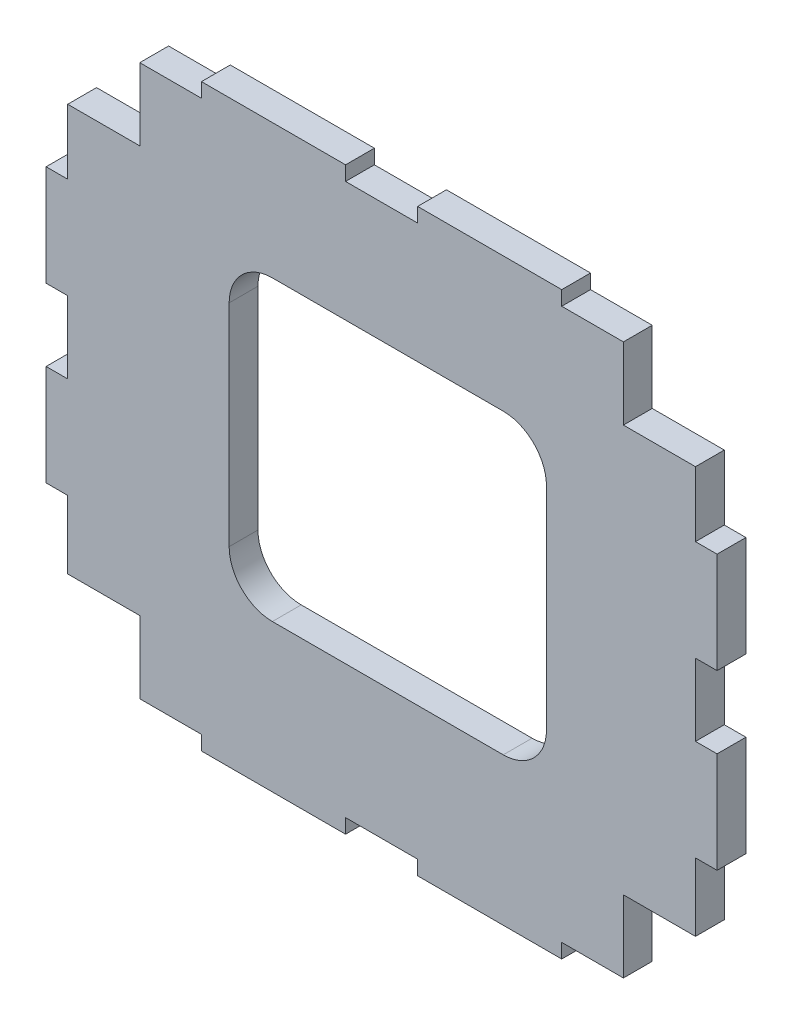
SolidWorks part; units mm, degrees
ref_plane "前视基准面" through (0, 0, 0) normal (0, 0, 1) x (1, 0, 0)
ref_plane "上视基准面" through (0, 0, 0) normal (0, 1, 0) x (1, 0, 0)
ref_plane "右视基准面" through (0, 0, 0) normal (1, 0, 0) x (0, 0, -1)
sketch "Model" plane through (0, 0, 0) normal (0, 0, 1) x (1, 0, 0)
  line L0 (45.0198, 33.9458) -> (28.9998, 33.9458)
  line L1 (28.9998, 13.2958) -> (45.0198, 13.2958)
  line L2 (48.0198, 30.9458) -> (48.0198, 16.2958)
  line L3 (25.9998, 30.9458) -> (25.9998, 16.2958)
  line L4 (19.7974, 42.2796) -> (24.0774, 42.2796)
  line L5 (24.0774, 42.2796) -> (24.0774, 43.28)
  line L6 (24.0774, 43.28) -> (34.0774, 43.28)
  line L7 (34.0774, 43.28) -> (34.0774, 42.2796)
  line L8 (34.0774, 42.2796) -> (39.0774, 42.2796)
  line L9 (39.0774, 42.2796) -> (39.0774, 43.28)
  line L10 (39.0774, 43.28) -> (49.0774, 43.28)
  line L11 (49.0774, 43.28) -> (49.0774, 42.2796)
  line L12 (49.0774, 42.2796) -> (53.3574, 42.2796)
  line L13 (19.7974, 4.0528) -> (24.0774, 4.0528)
  line L14 (24.0774, 4.0528) -> (24.0774, 3.0524)
  line L15 (24.0774, 3.0524) -> (34.0774, 3.0524)
  line L16 (34.0774, 3.0524) -> (34.0774, 4.0528)
  line L17 (34.0774, 4.0528) -> (39.0774, 4.0528)
  line L18 (39.0774, 4.0528) -> (39.0774, 3.0524)
  line L19 (39.0774, 3.0524) -> (49.0774, 3.0524)
  line L20 (49.0774, 3.0524) -> (49.0774, 4.0528)
  line L21 (49.0774, 4.0528) -> (53.3574, 4.0528)
  line L22 (13.2974, 13.7734) -> (13.2974, 20.7734)
  line L23 (13.2974, 25.7734) -> (13.2974, 32.7734)
  line L24 (14.7974, 37.2796) -> (19.7974, 37.2796)
  line L25 (19.7974, 37.2796) -> (19.7974, 42.2796)
  line L26 (14.7974, 9.0528) -> (19.7974, 9.0528)
  line L27 (19.7974, 9.0528) -> (19.7974, 4.0528)
  line L28 (14.7974, 37.2796) -> (14.7974, 32.7734)
  line L29 (14.7974, 32.7734) -> (13.2974, 32.7734)
  line L30 (13.2974, 32.7734) -> (13.2974, 25.7734)
  line L31 (13.2974, 25.7734) -> (14.7974, 25.7734)
  line L32 (14.7974, 25.7734) -> (14.7974, 20.7734)
  line L33 (14.7974, 20.7734) -> (13.2974, 20.7734)
  line L34 (13.2974, 20.7734) -> (13.2974, 13.7734)
  line L35 (13.2974, 13.7734) -> (14.7974, 13.7734)
  line L36 (14.7974, 13.7734) -> (14.7974, 9.0528)
  line L37 (59.8574, 13.7734) -> (59.8574, 20.7734)
  line L38 (59.8574, 25.7734) -> (59.8574, 32.7734)
  line L39 (58.3574, 37.2796) -> (53.3574, 37.2796)
  line L40 (53.3574, 37.2796) -> (53.3574, 42.2796)
  line L41 (58.3574, 9.0528) -> (53.3574, 9.0528)
  line L42 (53.3574, 9.0528) -> (53.3574, 4.0528)
  line L43 (58.3574, 37.2796) -> (58.3574, 32.7734)
  line L44 (58.3574, 32.7734) -> (59.8574, 32.7734)
  line L45 (59.8574, 32.7734) -> (59.8574, 25.7734)
  line L46 (59.8574, 25.7734) -> (58.3574, 25.7734)
  line L47 (58.3574, 25.7734) -> (58.3574, 20.7734)
  line L48 (58.3574, 20.7734) -> (59.8574, 20.7734)
  line L49 (59.8574, 20.7734) -> (59.8574, 13.7734)
  line L50 (59.8574, 13.7734) -> (58.3574, 13.7734)
  line L51 (58.3574, 13.7734) -> (58.3574, 9.0528)
  arc A0 (28.9998, 33.9458) -> (25.9998, 30.9458) centre (28.9998, 30.9458) ccw
  arc A1 (45.0198, 13.2958) -> (48.0198, 16.2958) centre (45.0198, 16.2958) ccw
  arc A2 (48.0198, 30.9458) -> (45.0198, 33.9458) centre (45.0198, 30.9458) ccw
  arc A3 (25.9998, 16.2958) -> (28.9998, 13.2958) centre (28.9998, 16.2958) ccw
extrude "凸台-拉伸1" add sketch "Model" along normal blind 2 contours L51 L50 L37 L48 L47 L46 L38 L44 L43 L39 L40 L12 L11 L10 L9 L8 L7 L6 L5 L4 L25 L24 L28 L29 L23 L31 L32 L33 L22 L35 L36 L26 L27 L13 L14 L15 L16 L17 L18 L19 L20 L21 L42 L41 A3 L3 A0 L0 A2 L2
